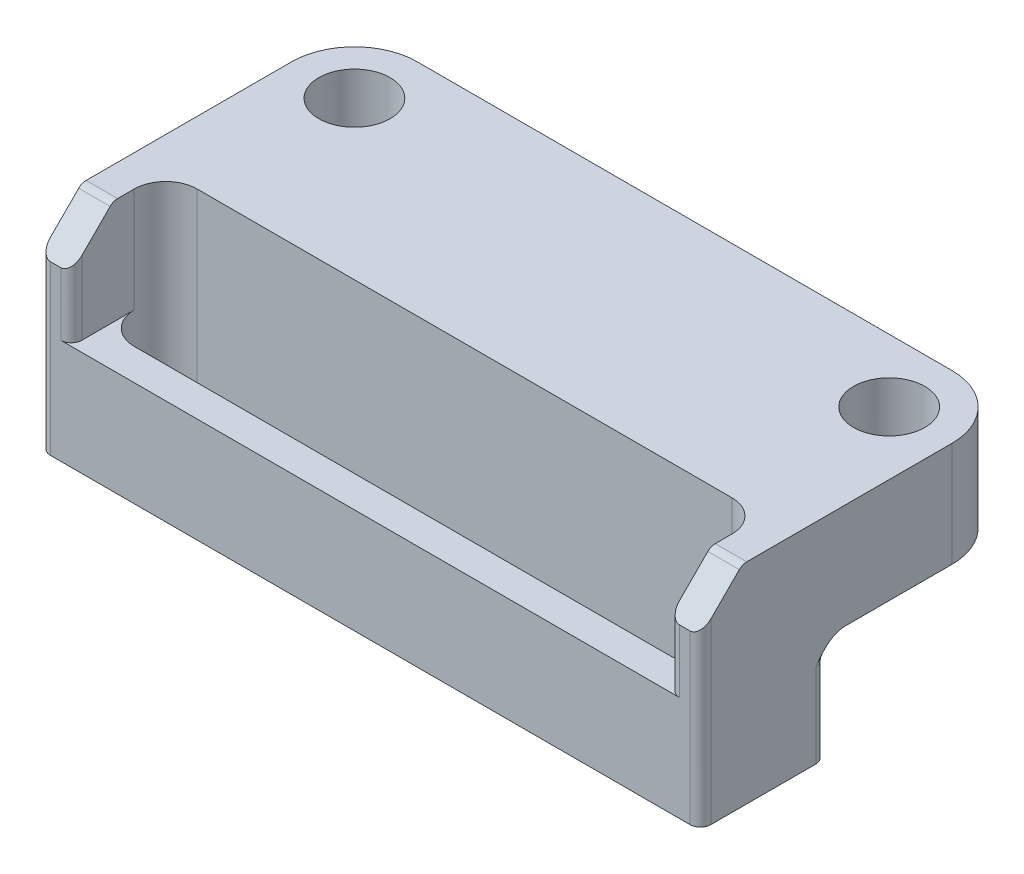
SolidWorks part; units mm, degrees
material "ABS"
ref_plane "Front Plane" through (0, 0, 0) normal (0, 0, 1) x (1, 0, 0)
ref_plane "Top Plane" through (0, 0, 0) normal (0, 1, 0) x (1, 0, 0)
ref_plane "Right Plane" through (0, 0, 0) normal (1, 0, 0) x (0, 0, -1)
sketch "Sketch1" plane through (0, 0, 0) normal (0, 1, 0) x (1, 0, 0)
  line L0 (-12.75, 3) -> (12.75, 3)
  line L1 (-15.75, 0) -> (-15.75, -12)
  line L2 (-15.75, -12) -> (15.75, -12)
  line L3 (0, 0) -> (0, 3) construction
  line L4 (15.75, 0) -> (15.75, -12)
  circle A0 centre (-12.75, 0) radius 3
  circle A1 centre (12.75, 0) radius 3
  point P11 (0, -12)
  dimension "D2" = 6
  dimension "D1" = 12.75
  dimension "D3" = 12
extrude "Boss-Extrude1" add sketch "Sketch1" along normal mid plane 10
hole_wizard "M3 Clearance Hole1" positions "Sketch2" profile "Sketch3" hole size "M3" standard "ANSI Metric" end condition through all
sketch "Sketch2" plane through (0, 5, 0) normal (0, 1, 0) x (1, 0, 0)
  point P0 (-12.75, 0)
  point P3 (12.75, 0)
sketch "Sketch3" plane through (-12.75, 5, 0) normal (1, 0, 0) x (0, 0, 1)
  line L0 (0, 0) -> (0, 10)
  line L1 (0, 10) -> (1.7, 10)
  line L2 (1.7, 10) -> (1.7, 0)
  line L5 (1.7, 0) -> (0, 0)
  line L11 (0, -6.35) -> (0, 107.95) construction
  dimension "Thru Hole Dia." = 3.4
  dimension "Thru Hole Depth" = 10
sketch "Sketch4" plane through (0, 5, 0) normal (0, 1, 0) x (1, 0, 0)
  line L0 (-12.75, -9) -> (12.75, -9) construction
  line L1 (-12.75, -7.5) -> (12.75, -7.5)
  line L2 (-12.75, -10.5) -> (12.75, -10.5)
  line L3 (-12.75, -9) -> (-12.75, 0) construction
  line L4 (12.75, -9) -> (12.75, 0) construction
  line L5 (-15.75, -12) -> (15.75, -12) construction
  arc A0 (-12.75, -7.5) -> (-12.75, -10.5) centre (-12.75, -9) ccw
  arc A1 (12.75, -10.5) -> (12.75, -7.5) centre (12.75, -9) ccw
  point P2 (0, -9)
  dimension "D1" = 3
  dimension "D2" = 3
extrude "Cut-Extrude1" cut sketch "Sketch4" against normal through all
sketch "Sketch5" plane through (15.75, 0, 0) normal (1, 0, 0) x (0, 0, -1)
  line L3 (-6, -5) -> (-6, 0)
  line L5 (-6, 0) -> (3, 0)
  line L6 (3, 5) -> (0, 5) construction
  line L7 (3, 5) -> (3, -5)
  line L12 (-6, -5) -> (3, -5)
  point P1 (-5.6321, -6.25)
  dimension "D1" = 5
  dimension "D2" = 9
extrude "Cut-Extrude2" cut sketch "Sketch5" against normal through all
ref_plane "Plane1" through (0, 0, 9) normal (0, 0, 1) x (1, 0, 0)
sketch "Sketch6" plane through (0, 0, 9) normal (0, 0, 1) x (1, 0, 0)
  line L0 (-12.75, 5) -> (-14.25, 5) construction
  line L2 (-12.75, 5) -> (-14.25, 5)
  line L3 (-14.25, 5) -> (-14.25, 0)
  line L4 (-14.25, 0) -> (14.25, 0)
  line L5 (-12.75, 5) -> (12.75, 5)
  line L6 (-15.75, 5) -> (15.75, 5) construction
  line L7 (0, 5) -> (0, 0) construction
  line L8 (14.25, 5) -> (14.25, 0)
  line L9 (12.75, 5) -> (14.25, 5)
extrude "Cut-Extrude5" cut sketch "Sketch6" along normal through all
chamfer "Chamfer1" distance 2 angle 45 2 edges at (15, 5, 12) (-15, 5, 12)
fillet "Fillet5" radius 0.5 8 edges at (-15.75, -2.5, 6) (15.75, -2.5, 6) (15.75, -1, 12) (14.25, 1.5, 12) (-14.25, 1.5, 12) (-15.75, -1, 12) (15, 5, 10) (-15, 5, 10)
fillet "Fillet6" radius 1 3 edges at (-15.6036, 0, 6.1464) (15.6036, 0, 6.1464) (0, 0, 6)
